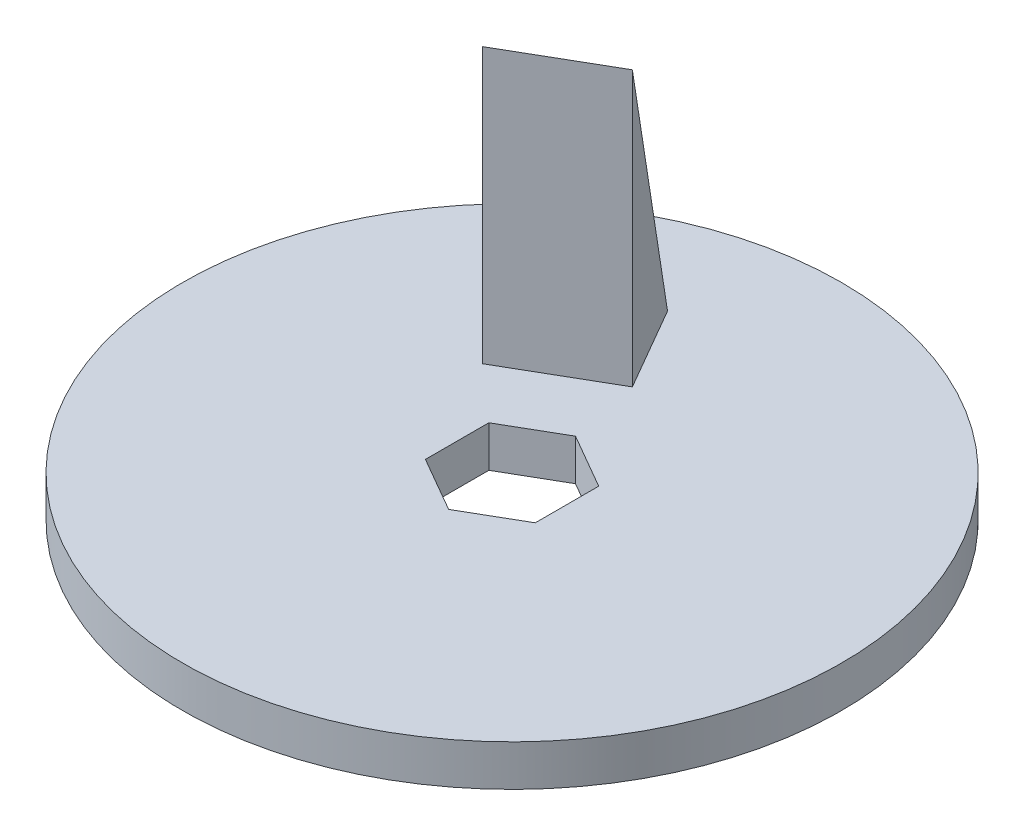
SolidWorks part; units mm, degrees
ref_plane "Front Plane" through (0, 0, 0) normal (0, 0, 1) x (1, 0, 0)
ref_plane "Top Plane" through (0, 0, 0) normal (0, 1, 0) x (1, 0, 0)
ref_plane "Right Plane" through (0, 0, 0) normal (1, 0, 0) x (0, 0, -1)
sketch "Sketch2" plane through (0, 0, 0) normal (0, 1, 0) x (1, 0, 0)
  line L0 (0, 0) -> (0, 152.4) construction
  line L1 (0, 29.3294) -> (-25.4, 14.6647)
  line L2 (-25.4, 14.6647) -> (-25.4, -14.6647)
  line L3 (-25.4, -14.6647) -> (0, -29.3294)
  line L4 (0, -29.3294) -> (25.4, -14.6647)
  line L5 (25.4, -14.6647) -> (25.4, 14.6647)
  line L6 (25.4, 14.6647) -> (0, 29.3294)
  line L7 (0, 0) -> (-152.4, 0) construction
  line L8 (0, 0) -> (152.4, 0) construction
  line L9 (0, 0) -> (0, -152.4) construction
  line L11 (-152.4, 0) -> (-139.7, 0)
  line L12 (-152.4, 0) -> (-152.4, 31.75)
  line L13 (-152.4, 31.75) -> (-139.7, 31.75)
  line L14 (-139.7, 0) -> (-139.7, 31.75)
  line L15 (0, 152.4) -> (-31.75, 152.4)
  line L16 (0, 152.4) -> (0, 139.7)
  line L17 (0, 139.7) -> (-31.75, 139.7)
  line L18 (-31.75, 152.4) -> (-31.75, 139.7)
  line L19 (152.4, 0) -> (139.7, 0)
  line L20 (152.4, 0) -> (152.4, -31.75)
  line L21 (152.4, -31.75) -> (139.7, -31.75)
  line L22 (139.7, 0) -> (139.7, -31.75)
  line L23 (0, -152.4) -> (31.75, -152.4)
  line L24 (0, -152.4) -> (0, -139.7)
  line L25 (0, -139.7) -> (31.75, -139.7)
  line L26 (31.75, -152.4) -> (31.75, -139.7)
  circle A0 centre (0, 0) radius 152.4
  circle A1 centre (0, 0) radius 25.4 construction
  dimension "D1" = 304.8
  dimension "D2" = 50.8
  dimension "D3" = 12.7
  dimension "D4" = 31.75
  dimension "D5" = 31.75
  dimension "D6" = 12.7
  dimension "D7" = 12.7
  dimension "D8" = 31.75
  dimension "D9" = 31.75
  dimension "D10" = 12.7
extrude "Boss-Extrude1" add sketch "Sketch2" along normal blind 19.05 contours L13 A0 L11 L14 | L16 A0 L18 L17 | L21 A0 L19 L22 | L24 A0 L26 L25 | L26 A0 L21 L22 L19 L16 L17 L18 L13 L14 L11 L24 L25 L6 L5 L4 L3 L2 L1
sketch "Sketch3" plane through (0, 19.05, 0) normal (0, 1, 0) x (1, 0, 0)
  line L0 (12.7, -21.997) -> (-12.7, 21.997) construction
  line L1 (0, 29.3294) -> (-25.4, 14.6647) construction
  line L2 (-70.6905, 25.178) -> (27.9893, 82.1508) construction
  line L3 (-12.7, 21.997) -> (-38.1, 65.9911)
  line L4 (-50.572, 36.7934) -> (-72.797, 75.2882)
  line L5 (-72.797, 75.2882) -> (-28.803, 100.6882)
  line L6 (-28.803, 100.6882) -> (-6.578, 62.1934)
  line L7 (-50.572, 36.7934) -> (-6.578, 62.1934)
  circle A0 centre (0, 0) radius 76.2 construction
  point P8 (0, 0)
  point P12 (-5.4993, 9.525)
  point P13 (-21.3506, 53.6644)
  point P15 (-12.7, 21.997)
  dimension "D1" = 113.9456
  dimension "D2" = 25.4
  dimension "D3" = 25.4
  dimension "D4" = 76.2
  dimension "D5" = 44.45
extrude "Boss-Extrude2" add sketch "Sketch3" along normal blind 127 contours L4 L7 L3 L5 | L3 L7 L6 L5
sketch "Sketch5" plane through (-21.997, 0, 12.7) normal (-0.866, 0, 0.5) x (0.5, 0, 0.866)
  line L0 (-101.6, 19.05) -> (-101.6, 146.05)
  line L1 (-101.6, 146.05) -> (-57.15, 146.05)
  line L2 (-57.15, 146.05) -> (-101.6, 19.05)
extrude "Cut-Extrude1" cut sketch "Sketch5" against normal through all
